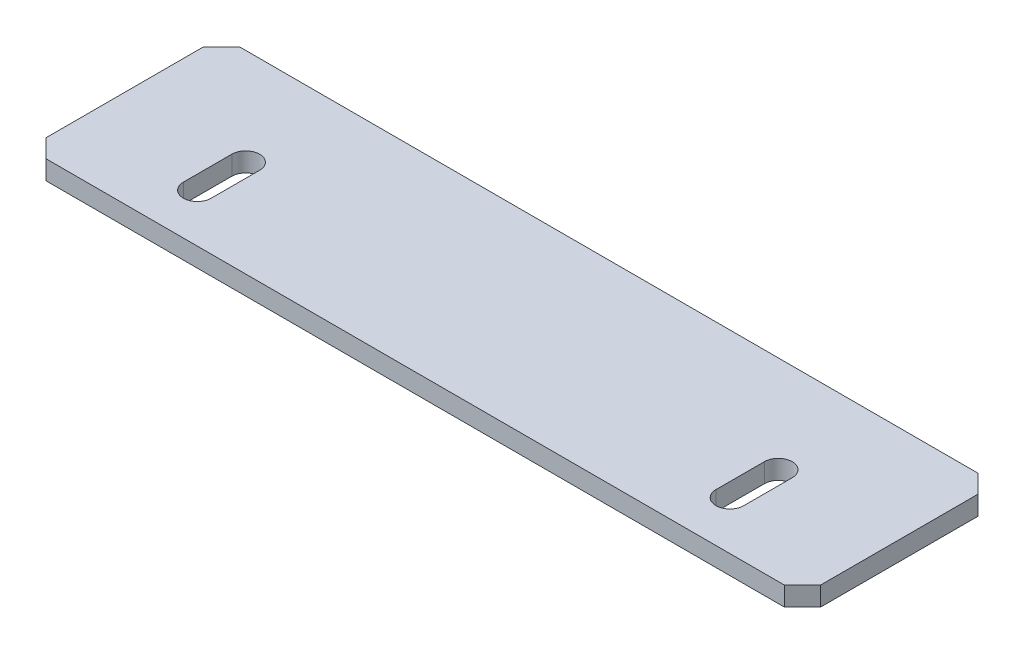
SolidWorks part; units mm, degrees
ref_plane "Front Plane" through (0, 0, 0) normal (0, 0, 1) x (1, 0, 0)
ref_plane "Top Plane" through (0, 0, 0) normal (0, 1, 0) x (1, 0, 0)
ref_plane "Right Plane" through (0, 0, 0) normal (1, 0, 0) x (0, 0, -1)
sketch "Sketch1" plane through (0, 0, 0) normal (0, 1, 0) x (1, 0, 0)
  line L0 (-320, 65) -> (-305, 80)
  line L1 (-305, 80) -> (305, 80)
  line L2 (-320, 65) -> (-320, -65)
  line L3 (-305, -80) -> (305, -80)
  line L4 (320, 65) -> (320, -65)
  line L5 (-320, 80) -> (320, -80) construction
  line L6 (-320, -80) -> (320, 80) construction
  line L7 (305, 80) -> (320, 65)
  line L8 (-320, -65) -> (-305, -80)
  line L9 (305, -80) -> (320, -65)
  line L10 (220, -40) -> (220, 0) construction
  line L11 (208.5, -40) -> (208.5, 0)
  line L12 (231.5, -40) -> (231.5, 0)
  line L13 (0, 225.5488) -> (0, -265.5356) construction
  line L16 (-220, -40) -> (-220, 0) construction
  line L17 (-208.5, -40) -> (-208.5, 0)
  line L18 (-231.5, -40) -> (-231.5, 0)
  arc A0 (208.5, -40) -> (231.5, -40) centre (220, -40) ccw
  arc A1 (231.5, 0) -> (208.5, 0) centre (220, 0) ccw
  arc A4 (-208.5, -40) -> (-231.5, -40) centre (-220, -40) cw
  arc A5 (-231.5, 0) -> (-208.5, 0) centre (-220, 0) cw
  point P0 (0, 0)
  point P16 (220, -20)
  point P25 (-220, -20)
  dimension "D14" = 11.5
  dimension "D1" = 160
  dimension "D2" = 640
  dimension "D3" = 15
  dimension "D4" = 45
  dimension "D5" = 15
  dimension "D6" = 45
  dimension "D7" = 15
  dimension "D8" = 45
  dimension "D9" = 15
  dimension "D10" = 45
  dimension "D11" = 40
  dimension "D12" = 40
  dimension "D13" = 100
extrude "Boss-Extrude1" add sketch "Sketch1" along normal mid plane 15.8
